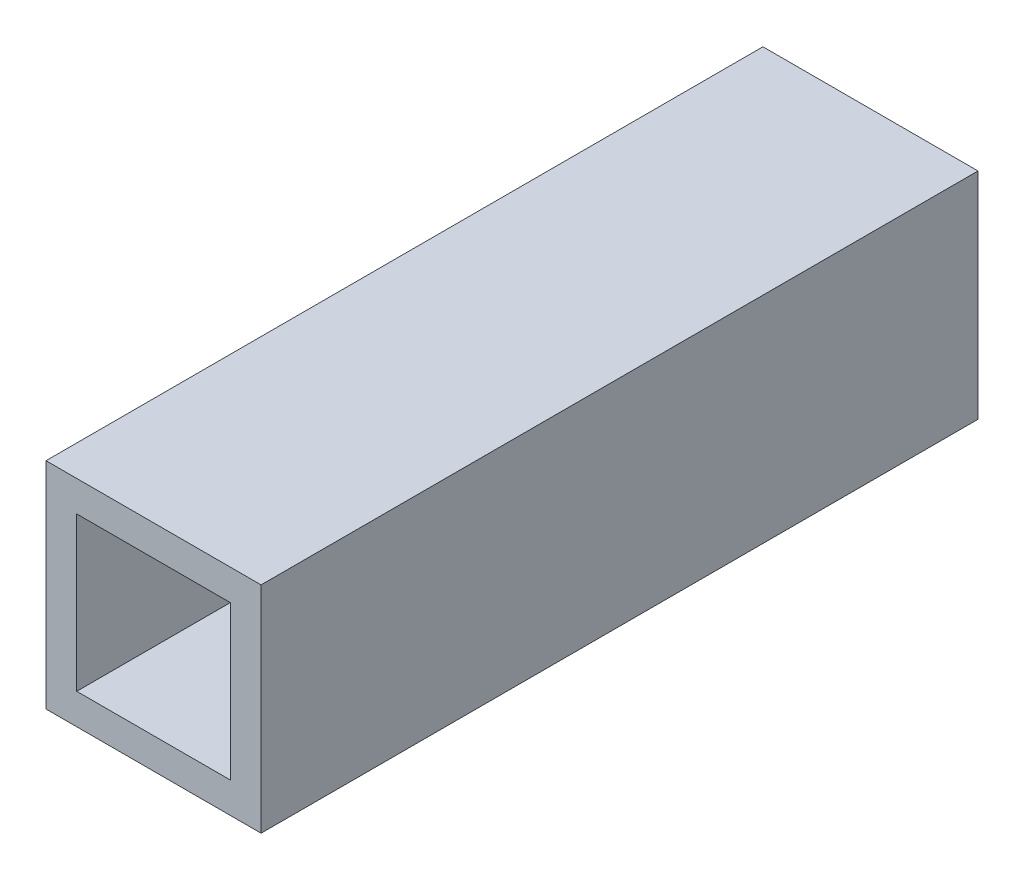
SolidWorks part; units mm, degrees
ref_plane "Alzado" through (0, 0, 0) normal (0, 0, 1) x (1, 0, 0)
ref_plane "Planta" through (0, 0, 0) normal (0, 1, 0) x (1, 0, 0)
ref_plane "Vista lateral" through (0, 0, 0) normal (1, 0, 0) x (0, 0, -1)
sketch "Croquis1" plane through (0, 0, 0) normal (0, 0, 1) x (1, 0, 0)
  line L0 (-7.5, -7.5) -> (7.5, -7.5)
  line L1 (-7.5, -7.5) -> (-7.5, 7.5)
  line L2 (-7.5, 7.5) -> (7.5, 7.5)
  line L3 (7.5, -7.5) -> (7.5, 7.5)
  line L4 (-7.5, -7.5) -> (7.5, 7.5) construction
  line L5 (-7.5, 7.5) -> (7.5, -7.5) construction
  line L6 (-10.5, -10.5) -> (10.5, -10.5)
  line L7 (-10.5, -10.5) -> (-10.5, 10.5)
  line L8 (-10.5, 10.5) -> (10.5, 10.5)
  line L9 (10.5, -10.5) -> (10.5, 10.5)
  line L10 (-10.5, -10.5) -> (10.5, 10.5) construction
  line L11 (-10.5, 10.5) -> (10.5, -10.5) construction
  point P0 (0, 0)
  point P5 (0, 0)
  dimension "D1" = 15
  dimension "D2" = 15
  dimension "D3" = 21
  dimension "D4" = 21
extrude "Saliente-Extruir1" add sketch "Croquis1" along normal blind 70
sketch "Croquis3" plane through (-10.5, 0, 0) normal (-1, 0, 0) x (0, 0, 1)
  line L0 (70, 10.5) -> (49, -10.5)
  line L1 (70, -10.5) -> (0, -10.5) construction
  line L2 (49, -10.5) -> (70, -10.5)
  line L3 (70, -10.5) -> (70, 10.5)
  dimension "D1" = 45
